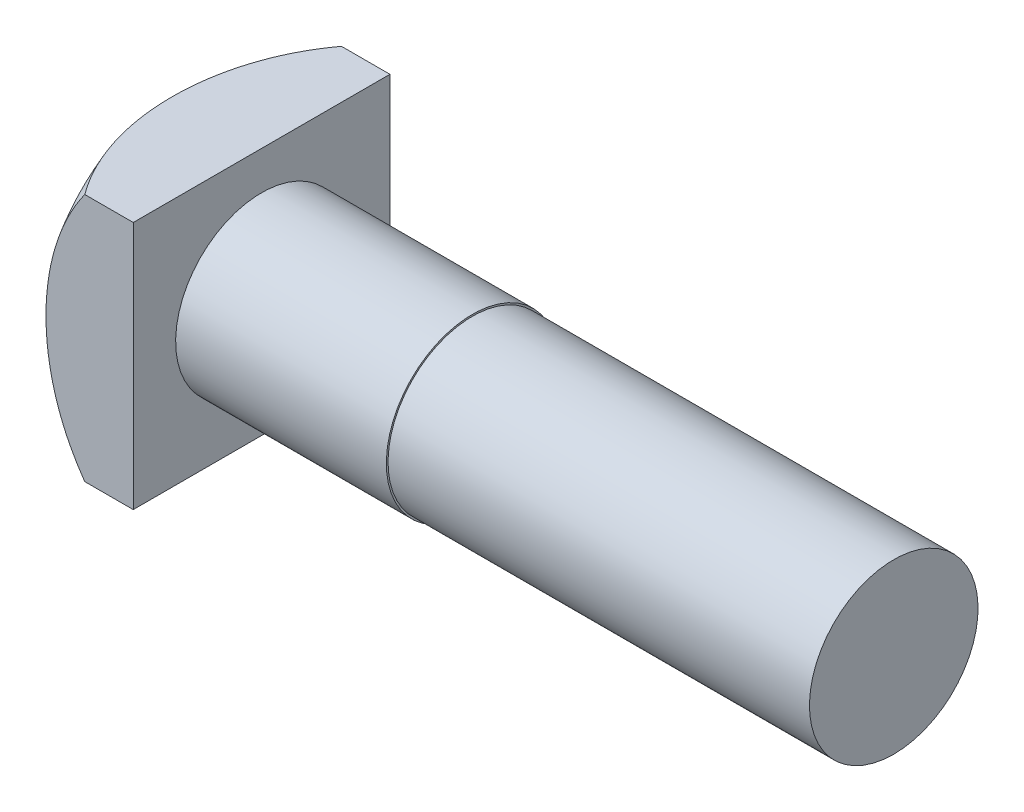
SolidWorks part; units mm, degrees
ref_plane "Front Plane" through (0, 0, 0) normal (0, 0, 1) x (1, 0, 0)
ref_plane "Top Plane" through (0, 0, 0) normal (0, 1, 0) x (1, 0, 0)
ref_plane "Right Plane" through (0, 0, 0) normal (1, 0, 0) x (0, 0, -1)
sketch "Sketch1" plane through (0, 0, 0) normal (0, 0, 1) x (1, 0, 0)
  line L0 (0, 0) -> (111.9124, 0) construction
  line L1 (111.9124, 0) -> (16.6624, 0)
  line L2 (111.9124, 0) -> (122.9535, 0) construction
  line L4 (111.9124, 0) -> (111.9124, 12.7)
  line L5 (16.6624, 12.954) -> (48.4124, 12.954)
  line L8 (16.6624, 0) -> (16.6624, 12.954)
  line L12 (48.4124, 12.7) -> (111.9124, 12.7)
  line L18 (48.4124, 12.7) -> (48.4124, 12.954)
revolve "Revolve1" add sketch "Sketch1" angle 360 about L0
sketch "Sketch2" plane through (0, 0, 0) normal (1, 0, 0) x (0, 0, -1)
  line L1 (-19.3372, 18.7343) -> (19.3372, 18.7343)
  line L2 (-19.3372, 18.7343) -> (-19.3372, -18.7343)
  line L3 (-19.3372, -18.7343) -> (19.3372, -18.7343)
  line L4 (19.3372, 18.7343) -> (19.3372, -18.7343)
  point P0 (0, 0)
  dimension "D1" = 53.848
extrude "Extrude1" add sketch "Sketch2" along normal blind 16.6624
sketch "Sketch3" plane through (0, 0, 0) normal (0, 0, 1) x (1, 0, 0)
  line L1 (0, 0) -> (0, 10.2582)
  line L2 (-5.3012, 31.4883) -> (-5.3012, 0)
  line L3 (0, 18.7343) -> (0, -18.7343) construction
  line L4 (0, 0) -> (-5.3012, 0)
  line L5 (-5.3012, 31.4883) -> (15.2102, 31.4883)
  arc A1 (0, 10.2582) -> (15.2102, 31.4883) centre (32.9238, 2.7337) cw
  point P0 (0, 0)
revolve "Cut-Revolve1" cut sketch "Sketch3" angle 360 about L4
ref_plane "Plane4" through (111.9124, 0, 0) normal (1, 0, 0) x (0, 0, -1)
